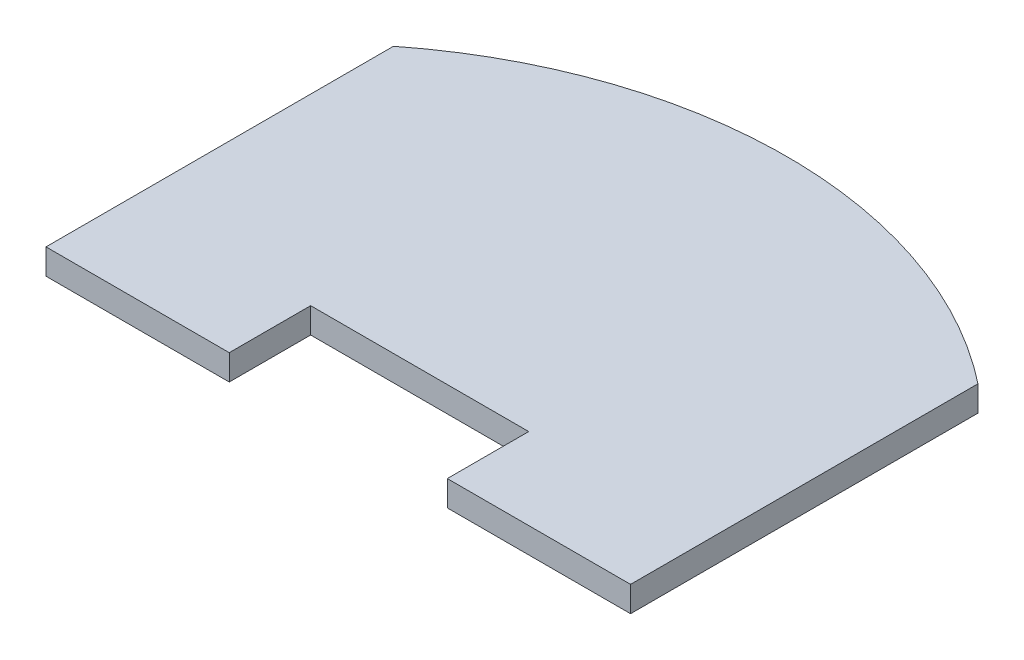
SolidWorks part; units mm, degrees
ref_plane "Front Plane" through (0, 0, 0) normal (0, 0, 1) x (1, 0, 0)
ref_plane "Top Plane" through (0, 0, 0) normal (0, 1, 0) x (1, 0, 0)
ref_plane "Right Plane" through (0, 0, 0) normal (1, 0, 0) x (0, 0, -1)
other "Center of Mass"
sketch "Sketch1" plane through (0, 0, 0) normal (0, 1, 0) x (1, 0, 0)
  line L1 (-51.0689, 4.15) -> (-51.0689, 64.8573)
  line L2 (51.0689, 4.15) -> (51.0689, 64.8573)
  line L3 (-51.0689, 4.15) -> (-19.05, 4.15)
  line L4 (0, 0) -> (101.6, 0) construction
  line L5 (0, 0) -> (-101.6, 0) construction
  line L9 (0, 9.525) -> (0, 14.2875) construction
  line L10 (-2.3813, 14.2875) -> (2.3813, 14.2875) construction
  line L11 (-2.3813, 14.2875) -> (-2.3813, 9.2225) construction
  line L12 (2.3813, 14.2875) -> (2.3813, 9.2225) construction
  line L18 (0, 9.525) -> (19.05, 9.525) construction
  line L24 (-19.05, 14.2875) -> (-19.05, -14.224) construction
  line L25 (-19.05, -14.224) -> (19.05, -14.224) construction
  line L26 (19.05, 14.2875) -> (19.05, -14.224) construction
  line L27 (0, 9.525) -> (-19.05, 9.525) construction
  line L30 (19.05, 14.2875) -> (-19.05, 14.2875) construction
  line L31 (19.05, 4.15) -> (51.0689, 4.15)
  line L33 (19.05, 14.2875) -> (19.05, 4.15)
  line L35 (-19.05, 14.2875) -> (-19.05, 4.15)
  line L36 (19.05, 18.374) -> (-19.05, 18.374)
  line L37 (19.05, 18.374) -> (19.05, 14.2875)
  line L38 (-19.05, 18.374) -> (-19.05, 14.2875)
  circle A0 centre (0, 0) radius 101.6 construction
  circle A1 centre (0, 0) radius 88.9 construction
  circle A2 centre (0, 0) radius 82.55 construction
  arc A3 (-51.0689, 64.8573) -> (51.0689, 64.8573) centre (0, 0) cw
  arc A4 (-51.0689, -64.8573) -> (51.0689, -64.8573) centre (0, 0) ccw construction
  circle A5 centre (0, 0) radius 9.525 construction
  point P8 (0, 0)
  point P22 (0, 14.2875)
  dimension "D1" = 165.1
  dimension "D2" = 203.2
  dimension "D3" = 6.35
  dimension "D4" = 19.05
  dimension "D10" = 110.1238
  dimension "D5" = 4.7625
  dimension "D6" = 4.7625
  dimension "D7" = 38.1
  dimension "D8" = 38.1
  dimension "D9" = 14.224
  dimension "D11" = 4.15
  dimension "D12" = 14.224
ref_point "Point1"
extrude "Boss-Extrude2" add sketch "Sketch1" along normal blind 4.445
